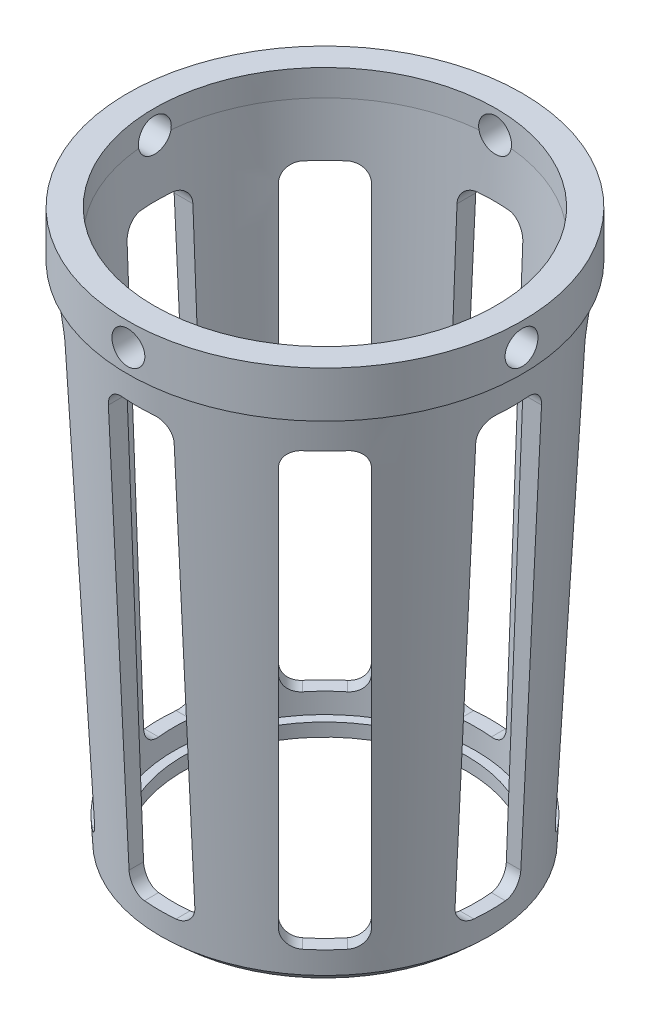
SolidWorks part; units mm, degrees
material "6061-T6 (SS)"
ref_plane "Front Plane" through (0, 0, 0) normal (0, 0, 1) x (1, 0, 0)
ref_plane "Top Plane" through (0, 0, 0) normal (0, 1, 0) x (1, 0, 0)
ref_plane "Right Plane" through (0, 0, 0) normal (1, 0, 0) x (0, 0, -1)
sketch "Sketch2" plane through (0, 0, 0) normal (0, 0, 1) x (1, 0, 0)
  line L0 (0, 0) -> (0, 107.95) construction
  line L1 (0, 0) -> (27.3304, 0) construction
  line L2 (0, 0) -> (31.623, 0)
  line L3 (0, 107.95) -> (38.0746, 107.95) construction
  line L4 (27.3304, 0) -> (27.3304, 2.54)
  line L5 (27.3304, 2.54) -> (29.083, 2.54)
  line L6 (31.623, 0) -> (36.4998, 99.06)
  line L7 (38.0746, 107.95) -> (32.9946, 107.95)
  line L8 (32.9946, 107.95) -> (32.9946, 102.87)
  line L9 (32.9946, 102.87) -> (29.083, 2.54)
  line L10 (38.0746, 107.95) -> (38.0746, 99.06)
  line L11 (38.0746, 99.06) -> (36.4998, 99.06)
  dimension "D1" = 31.623
  dimension "D2" = 27.3304
  dimension "D3" = 107.95
  dimension "D4" = 108.1426
  dimension "D5" = 100.33
  dimension "D6" = 32.9946
  dimension "D7" = 100.4062
revolve "Revolve2" add sketch "Sketch2" angle 360 about L0
sketch "Sketch5" plane through (0, 0, 0) normal (0, 0, 1) x (1, 0, 0)
  line L0 (0, 107.95) -> (0, 99.06)
  line L1 (32.9946, 107.95) -> (-32.9946, 107.95) construction
  line L2 (-36.4998, 99.06) -> (36.4998, 99.06) construction
  circle A0 centre (0, 103.505) radius 3.175
extrude "Cut-Extrude2" cut sketch "Sketch5" against normal blind 45.212 contours L0 A0 | L0 A0
pattern_circular "CirPattern2" count 4 over 360 about axis through (0, 0, 0) along (0, -1, 0) of "Cut-Extrude2"
sketch "Sketch6" plane through (0, 0, 0) normal (1, 0, 0) x (0, 0, -1)
  line L0 (0, 107.95) -> (0, 92.71)
  line L1 (38.0746, 107.95) -> (-38.0746, 107.95) construction
  line L2 (0, 92.71) -> (-6.35, 92.71)
  line L3 (0, 92.71) -> (6.35, 92.71)
  line L4 (6.35, 92.71) -> (6.35, 6.35)
  line L5 (6.35, 6.35) -> (-6.35, 6.35)
  line L6 (-6.35, 6.35) -> (-6.35, 92.71)
extrude "Cut-Extrude3" cut sketch "Sketch6" against normal blind 124.206 contours L3 L4 L5 L6 L2
pattern_circular "CirPattern3" count 8 over 360 about axis through (0, 0, 0) along (0, 1, 0) of "Cut-Extrude3"
chamfer "Chamfer1" distance 1.905 angle 45 1 edges at (0, 0, -31.623)
fillet "Fillet1" radius 3.302 32 edges at (-25.6437, 6.35, 16.6635) (-6.35, 6.35, 29.9157) (16.6635, 6.35, 25.6437) (29.9157, 6.35, 6.35) (25.6437, 6.35, -16.6635) (6.35, 6.35, -29.9157) (-16.6635, 6.35, 25.6437) (-17.2713, 62.576, 26.2516) (-16.6635, 6.35, -25.6437) (-25.6437, 6.35, -16.6635) (-26.2516, 62.576, -17.2713) (16.6635, 6.35, -25.6437) (17.2713, 62.576, -26.2516) (25.6437, 6.35, 16.6635) (26.2516, 62.576, 17.2713) (6.35, 6.35, 29.9157) (29.9157, 6.35, -6.35) (-6.35, 6.35, -29.9157) (-29.9157, 6.35, -6.35) (-29.9157, 6.35, 6.35) (-19.7968, 67.1512, -28.777) (28.777, 67.1512, -19.7968) (19.7968, 67.1512, 28.777) (-28.777, 67.1512, 19.7968)
fillet "Fillet2" radius 3.302 32 edges at (19.41, 92.71, -28.3902) (33.7999, 92.71, -6.35) (28.3902, 92.71, 19.41) (6.35, 92.71, 33.7999) (-19.41, 92.71, 28.3902) (-28.3902, 92.71, -19.41) (-28.3902, 92.71, 19.41) (-25.334, 30.0076, 16.3537) (-6.35, 92.71, -33.7999) (-6.35, 92.71, 33.7999) (19.41, 92.71, 28.3902) (16.3537, 30.0076, 25.334) (33.7999, 92.71, 6.35) (28.3902, 92.71, -19.41) (25.334, 30.0076, -16.3537) (6.35, 92.71, -33.7999) (-19.41, 92.71, -28.3902) (-16.3537, 30.0076, -25.334) (-33.7999, 92.71, 6.35) (-33.7999, 92.71, -6.35) (-27.2411, 23.8141, -18.2609) (18.2609, 23.8141, -27.2411) (27.2411, 23.8141, 18.2609) (-18.2609, 23.8141, 27.2411)
